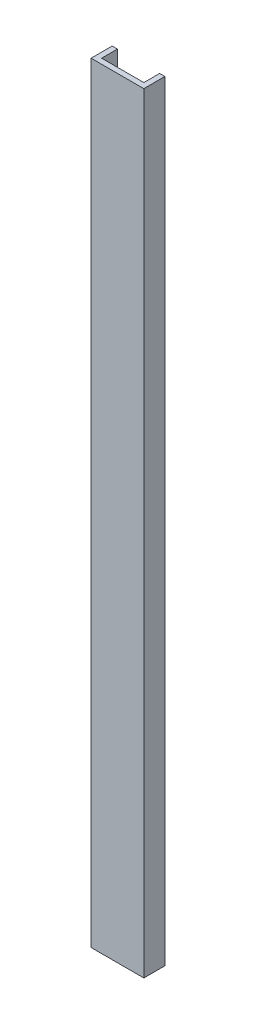
SolidWorks part; units mm, degrees
ref_plane "Front Plane" through (0, 0, 0) normal (0, 0, 1) x (1, 0, 0)
ref_plane "Top Plane" through (0, 0, 0) normal (0, 1, 0) x (1, 0, 0)
ref_plane "Right Plane" through (0, 0, 0) normal (1, 0, 0) x (0, 0, -1)
sketch "Sketch1" plane through (0, 0, 0) normal (0, 1, 0) x (1, 0, 0)
  line L0 (3.175, 3.175) -> (3.175, 12.7)
  line L1 (0, 0) -> (31.75, 0)
  line L2 (0, 0) -> (0, 12.7)
  line L4 (31.75, 0) -> (31.75, 12.7)
  line L5 (3.175, 3.175) -> (28.575, 3.175)
  line L6 (28.575, 3.175) -> (28.575, 12.7)
  line L7 (0, 12.7) -> (3.175, 12.7)
  line L8 (31.75, 12.7) -> (28.575, 12.7)
  dimension "D1" = 31.75
  dimension "D2" = 12.7
  dimension "D3" = 3.175
extrude "Boss-Extrude1" add sketch "Sketch1" along normal blind 463.6135
